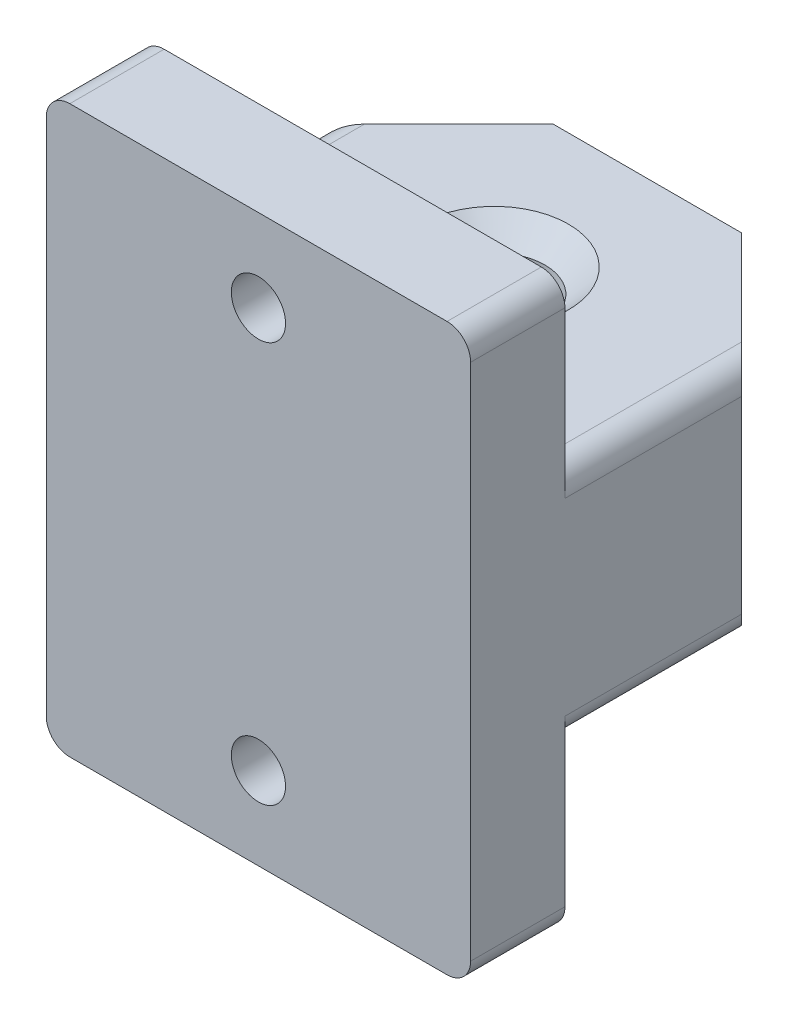
SolidWorks part; units mm, degrees
ref_plane "前视基准面" through (0, 0, 0) normal (0, 0, 1) x (1, 0, 0)
ref_plane "上视基准面" through (0, 0, 0) normal (0, 1, 0) x (1, 0, 0)
ref_plane "右视基准面" through (0, 0, 0) normal (1, 0, 0) x (0, 0, -1)
sketch "草图1" plane through (0, 0, 0) normal (0, 0, 1) x (1, 0, 0)
  line L1 (-9, -5) -> (9, -5)
  line L2 (-9, -5) -> (-9, 5)
  line L3 (-9, 5) -> (9, 5)
  line L4 (9, -5) -> (9, 5)
  line L5 (-9, -5) -> (9, 5) construction
  line L6 (-9, 5) -> (9, -5) construction
  point P0 (0, 0)
  dimension "D1" = 10
  dimension "D2" = 18
extrude "凸台-拉伸1" add sketch "草图1" along normal blind 23
sketch "草图3" plane through (0, 5, 0) normal (0, 1, 0) x (1, 0, 0)
  line L0 (0, 0) -> (0, -23) construction
  line L1 (9, -23) -> (-9, -23) construction
  line L2 (9, -11.5) -> (-9, -11.5) construction
  line L3 (9, -23) -> (9, 0) construction
  line L4 (-9, -23) -> (-9, 0) construction
  circle A0 centre (0, -13) radius 2.15
  dimension "D1" = 4.3
  dimension "D2" = 10
extrude "切除-拉伸1" cut sketch "草图3" against normal blind 23
fillet "圆角1" radius 1 4 edges at (9, -5, 11.5) (9, 5, 11.5) (-9, 5, 11.5) (-9, -5, 11.5)
sketch "草图4" plane through (0, 5, 0) normal (0, 1, 0) x (1, 0, 0)
  line L0 (9, 0) -> (9, -23) construction
  line L1 (-9, 0) -> (9, 0)
  line L2 (-9, 0) -> (-9, -6.5)
  line L3 (-9, -6.5) -> (9, -6.5)
  line L4 (9, 0) -> (9, -6.5)
  dimension "D1" = 6.5
extrude "切除-拉伸2" cut sketch "草图4" against normal blind 23
sketch "草图5" plane through (0, 0, 23) normal (0, 0, 1) x (1, 0, 0)
  line L11 (-9, 4) -> (-9, -4) construction
  line L12 (-9, 0) -> (9, 0)
  line L13 (-9, 0) -> (-9, 12)
  line L14 (-9, 12) -> (9, 12)
  line L15 (9, 0) -> (9, 12)
  dimension "D1" = 12
  dimension "D2" = 18
extrude "凸台-拉伸2" add sketch "草图5" against normal blind 4
sketch "草图6" plane through (0, 0, 19) normal (0, 0, -1) x (-1, 0, 0)
  line L0 (-9, 12) -> (9, 12) construction
  circle A0 centre (0, 8.5) radius 1.15
  dimension "D1" = 2.3
  dimension "D2" = 3.5
extrude "切除-拉伸3" cut sketch "草图6" against normal blind 4
fillet "圆角2" radius 1 2 edges at (9, 12, 21) (-9, 12, 21)
chamfer "倒角1" distance 1 angle 45 3 edges at (-1.15, 8.5, 19) (0, -5, 15.15) (0, 5, 15.15)
mirror "镜向1" about plane through (0, 0, 0) normal (0, 1, 0) of "凸台-拉伸2", "切除-拉伸3", "圆角2"
chamfer "倒角2" distance 0.5 angle 45 1 edges at (-1.15, -8.5, 19)
sketch "草图7" plane through (0, 5, 0) normal (0, 1, 0) x (1, 0, 0)
  line L0 (-9, -11.5) -> (-4, -6.5)
  line L1 (-9, -19) -> (-9, -6.5) construction
  line L2 (-8, -6.5) -> (8, -6.5) construction
  line L3 (0, -23) -> (0, -6.5) construction
  line L4 (8, -23) -> (-8, -23) construction
  line L5 (-9, -11.5) -> (-9, -6.5)
  line L6 (-9, -6.5) -> (-4, -6.5)
  line L7 (9, -11.5) -> (4, -6.5)
  line L8 (9, -11.5) -> (9, -6.5)
  line L9 (9, -6.5) -> (4, -6.5)
  dimension "D1" = 5
extrude "切除-拉伸4" cut sketch "草图7" against normal blind 10
